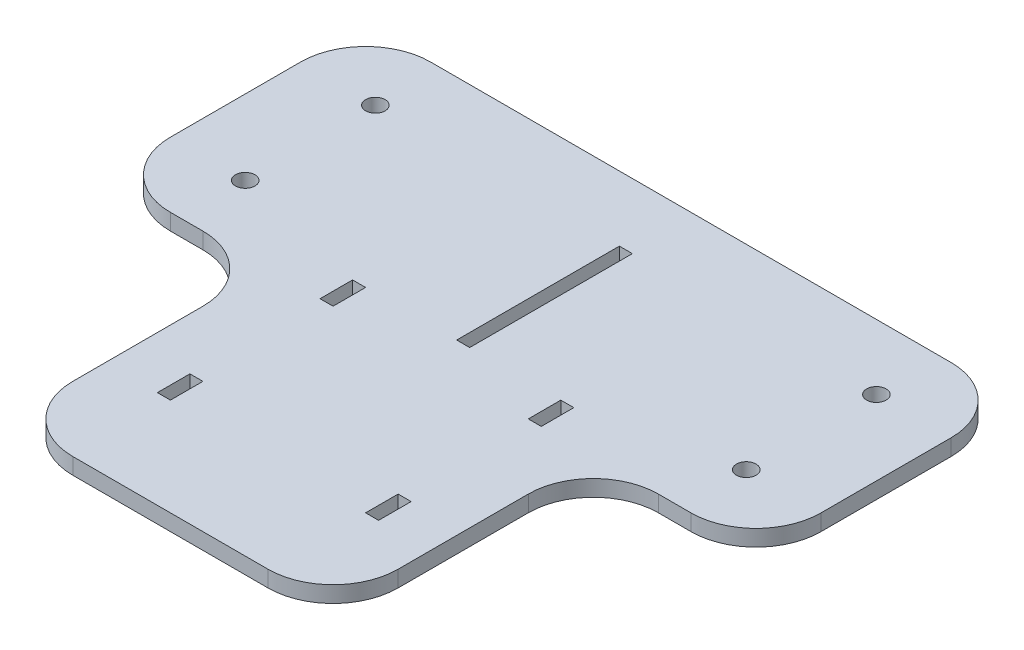
SolidWorks part; units mm, degrees
material "Maple"
ref_plane "Front Plane" through (0, 0, 0) normal (0, 0, 1) x (1, 0, 0)
ref_plane "Top Plane" through (0, 0, 0) normal (0, 1, 0) x (1, 0, 0)
ref_plane "Right Plane" through (0, 0, 0) normal (1, 0, 0) x (0, 0, -1)
sketch "Sketch1" plane through (0, 0, 0) normal (0, 1, 0) x (1, 0, 0)
  line L0 (-50, 0) -> (50, 0) construction
  line L1 (-50, -40) -> (50, -40) construction
  line L2 (-50, -40) -> (-50, 40) construction
  line L3 (-50, 40) -> (50, 40)
  line L4 (50, -40) -> (50, 40) construction
  line L5 (-50, -40) -> (50, 40) construction
  line L6 (-50, 40) -> (50, -40) construction
  line L7 (-25, 0) -> (-25, -40)
  line L8 (0, 14.902) -> (0, -12.8852) construction
  line L9 (25, 0) -> (25, -40)
  line L10 (-50, 40) -> (-50, 0)
  line L11 (-50, 0) -> (-25, 0)
  line L12 (-25, -40) -> (25, -40)
  line L13 (25, 0) -> (50, 0)
  line L14 (17, -25) -> (17, -20)
  line L15 (-17, -25) -> (-15, -25)
  line L16 (-17, -25) -> (-17, -20)
  line L17 (-17, -20) -> (-15, -20)
  line L18 (-15, -25) -> (-15, -20)
  line L19 (-17, -25) -> (-15, -20) construction
  line L20 (-17, -20) -> (-15, -25) construction
  line L21 (17, -25) -> (15, -25)
  line L22 (15, -25) -> (15, -20)
  line L23 (17, -20) -> (15, -20)
  line L24 (-15, 0) -> (-15, 5)
  line L25 (-17, 5) -> (-15, 5)
  line L26 (-17, 0) -> (-17, 5)
  line L27 (-17, 0) -> (-15, 0)
  line L28 (17, 0) -> (17, 5)
  line L29 (17, 5) -> (15, 5)
  line L30 (15, 0) -> (15, 5)
  line L31 (17, 0) -> (15, 0)
  line L32 (50, 0) -> (50, 40)
  line L33 (-1, 30) -> (1, 30)
  line L34 (-1, 30) -> (-1, 5)
  line L35 (-1, 5) -> (1, 5)
  line L36 (1, 30) -> (1, 5)
  line L37 (-1, 30) -> (1, 5) construction
  line L38 (-1, 5) -> (1, 30) construction
  circle A0 centre (-38.5, 30) radius 1.5
  circle A1 centre (38.5, 30) radius 1.5
  circle A2 centre (-38.5, 10) radius 1.5
  circle A3 centre (38.5, 10) radius 1.5
  point P0 (0, 0)
  point P14 (-16, -22.5)
  point P23 (0, 17.5)
  dimension "D13" = 3
  dimension "D1" = 80
  dimension "D2" = 100
  dimension "D3" = 50
  dimension "D5" = 25
  dimension "D6" = 5
  dimension "D7" = 20
  dimension "D8" = 15
  dimension "D9" = 30
  dimension "D10" = 2
  dimension "D11" = 10
  dimension "D14" = 20
  dimension "D15" = 77
  dimension "D16" = 10
  dimension "D4" = 2
  dimension "D12" = 2
extrude "Boss-Extrude1" add sketch "Sketch1" along normal mid plane 2.5
fillet "Fillet1" radius 10 8 edges at (50, 0, 0) (25, 0, 0) (25, 0, 40) (-25, 0, 40) (-25, 0, 0) (-50, 0, -40) (50, 0, -40) (-50, 0, 0)
